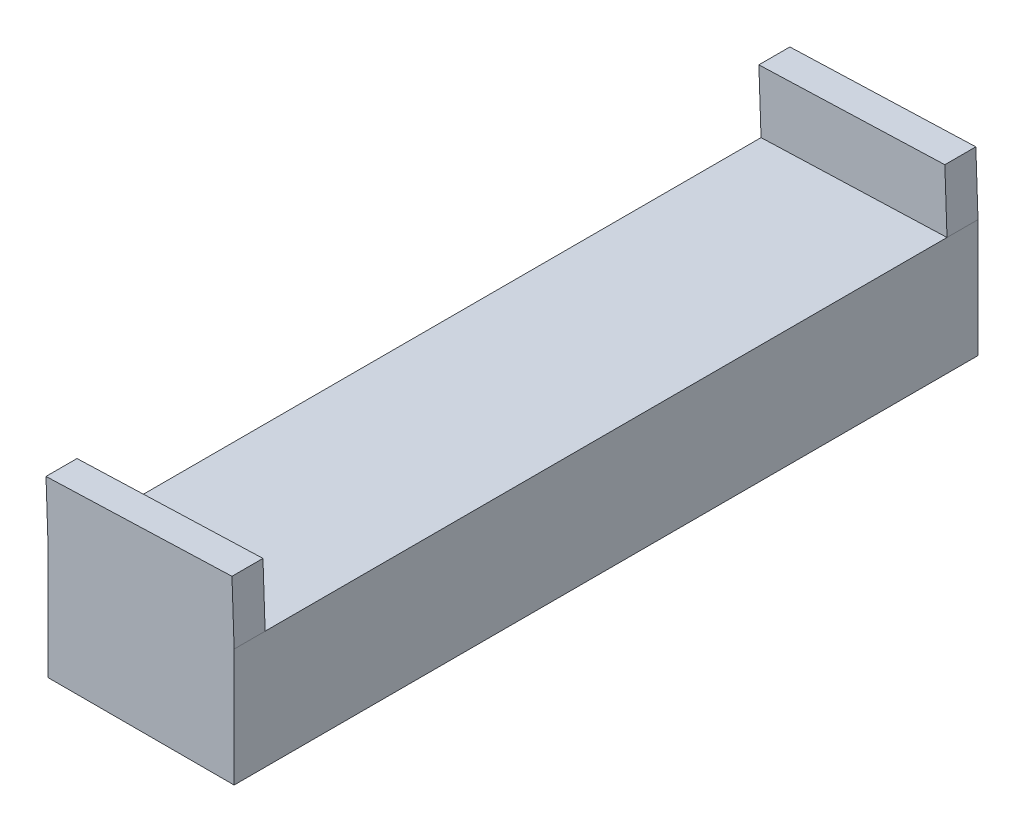
SolidWorks part; units mm, degrees
ref_plane "Спереди" through (0, 0, 0) normal (0, 0, 1) x (1, 0, 0)
ref_plane "Сверху" through (0, 0, 0) normal (0, 1, 0) x (1, 0, 0)
ref_plane "Справа" through (0, 0, 0) normal (1, 0, 0) x (0, 0, -1)
sketch "Эскиз1" plane through (708.7345, 0, -6544.7608) normal (0, 1, 0) x (1, 0, 0)
  line L1 (0, 0) -> (30, 0)
  line L2 (0, 0) -> (0, -120)
  line L3 (0, -120) -> (30, -120)
  line L4 (30, 0) -> (30, -120)
  dimension "D1" = 120
  dimension "D2" = 30
extrude "Бобышка-Вытянуть1" add sketch "Эскиз1" along normal blind 19
sketch "Эскиз3" plane through (0, 0, -6424.7608) normal (0, 0, 1) x (1, 0, 0)
  line L0 (738.7345, 19) -> (708.7345, 17.9524)
  line L1 (708.7345, 19) -> (708.7345, 0) construction
  line L2 (708.7345, 19) -> (738.7345, 19) construction
  line L3 (708.7345, 17.9524) -> (708.7345, 19)
  line L4 (708.7345, 19) -> (738.7345, 19)
  dimension "D1" = 2
extrude "Вырез-Вытянуть1" cut sketch "Эскиз3" against normal through all
sketch "Эскиз4" plane through (0.2371, -6.7889, 0) normal (-0.0349, 0.9994, 0) x (0.9994, 0.0349, 0)
  line L0 (708.9293, 6544.7608) -> (708.9293, 6424.7608) construction
  line L1 (708.9293, 6539.7608) -> (738.9476, 6539.7608)
  line L2 (708.9293, 6539.7608) -> (708.9293, 6544.7608)
  line L3 (708.9293, 6544.7608) -> (738.9476, 6544.7608)
  line L4 (738.9476, 6539.7608) -> (738.9476, 6544.7608)
  line L6 (738.9476, 6424.7608) -> (708.9293, 6424.7608)
  line L7 (738.9476, 6424.7608) -> (738.9476, 6429.7608)
  line L8 (738.9476, 6429.7608) -> (708.9293, 6429.7608)
  line L9 (708.9293, 6424.7608) -> (708.9293, 6429.7608)
  dimension "D1" = 5
  dimension "D2" = 5
extrude "Бобышка-Вытянуть2" add sketch "Эскиз4" along normal blind 10
